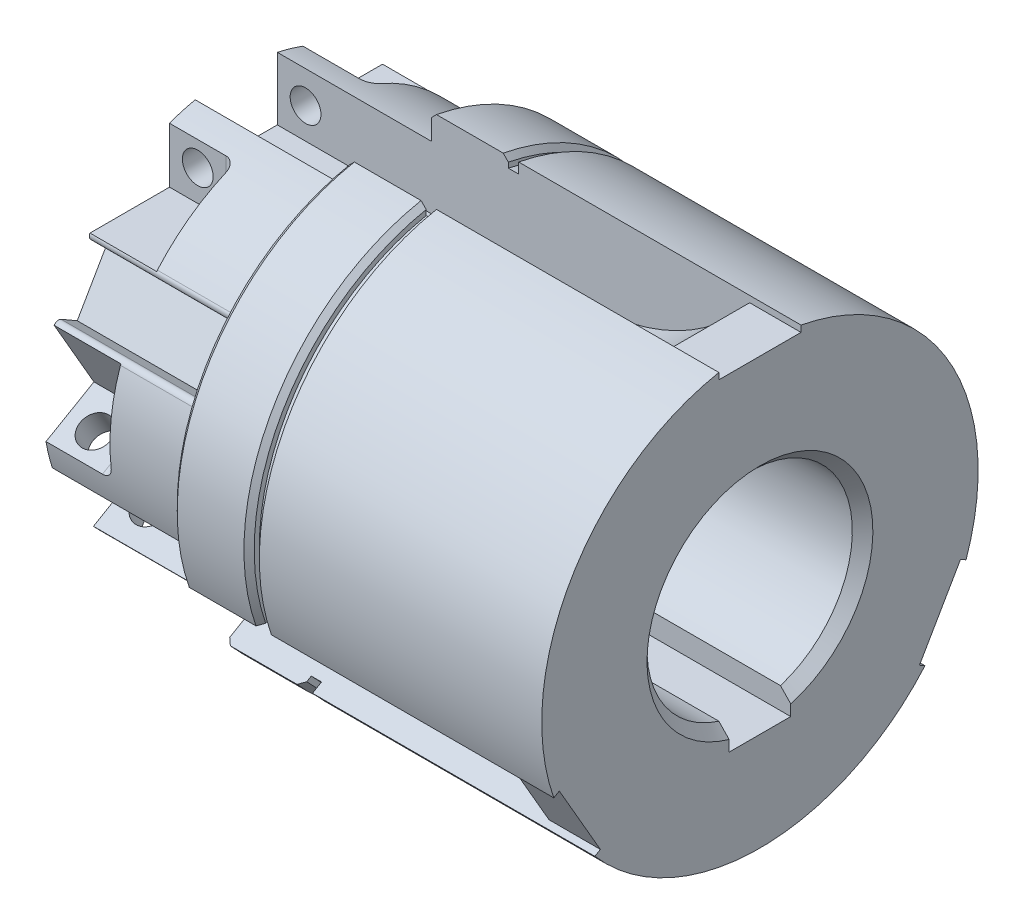
SolidWorks part; units mm, degrees
material "1.0060 (E335)"
ref_plane "Front Plane" through (0, 0, 0) normal (0, 0, 1) x (1, 0, 0)
ref_plane "Top Plane" through (0, 0, 0) normal (0, 1, 0) x (1, 0, 0)
ref_plane "Right Plane" through (0, 0, 0) normal (1, 0, 0) x (0, 0, -1)
sketch "Sketch1" plane through (0, 0, 0) normal (0, 0, 1) x (1, 0, 0)
  line L0 (-534.701, 0) -> (26200.3507, 0) construction
  line L1 (0, 20) -> (0, 42.5)
  line L2 (0, 20) -> (-102, 20)
  line L3 (0, 42.5) -> (-55, 42.5)
  line L4 (-55, 42.5) -> (-55, 40.5)
  line L5 (-55, 40.5) -> (-57, 40.5)
  line L6 (-57, 40.5) -> (-57, 42.5)
  line L7 (-57, 42.5) -> (-72, 42.5)
  line L8 (-72, 42.5) -> (-72, 37.6)
  line L9 (-72, 37.6) -> (-102, 37.6)
  line L10 (-102, 37.6) -> (-102, 20)
  dimension "D1" = 40
  dimension "D2" = 75.2
  dimension "D3" = 2
  dimension "D4" = 2
  dimension "D5" = 15
  dimension "D7" = 85
  dimension "D8" = 30
  dimension "D9" = 55
revolve "Revolve1" add sketch "Sketch1" angle 360 about L0
sketch "Sketch3" plane through (0, 0, 0) normal (0, 0, 1) x (1, 0, 0)
  line L0 (-102, 24.5) -> (-42, 24.5)
  line L1 (-102, 37.6) -> (-102, -37.6) construction
  line L2 (0, 42.5) -> (-55, 42.5) construction
  line L3 (0, 42.5) -> (-55, 42.5)
  line L4 (-57, -42.5) -> (-57, 42.5) construction
  line L5 (-55, 42.5) -> (-55, -42.5) construction
  line L6 (-57, 40.5) -> (-57, 42.5)
  line L7 (-55, 42.5) -> (-55, 40.5)
  line L8 (-55, 40.5) -> (-57, 40.5) construction
  line L9 (-55, 40.5) -> (-57, 40.5)
  line L10 (-72, 37.6) -> (-102, 37.6) construction
  line L11 (-72, 42.5) -> (-72, -42.5) construction
  line L12 (-57, 42.5) -> (-72, 42.5) construction
  line L13 (-72, 37.6) -> (-102, 37.6)
  line L14 (-72, 42.5) -> (-72, 37.6)
  line L15 (-57, 42.5) -> (-72, 42.5)
  line L16 (-102, 37.6) -> (-102, 24.5)
  line L17 (-10, 40.5) -> (0, 40.5)
  line L18 (0, -42.5) -> (0, 42.5) construction
  line L19 (0, 40.5) -> (0, 42.5)
  arc A0 (-42, 24.5) -> (-10, 40.5) centre (-42, 64.5) ccw
  dimension "D2" = 40
  dimension "D1" = 18
  dimension "D3" = 2
  dimension "D4" = 60
extrude "Cut-Extrude1" cut sketch "Sketch3" against normal mid plane 16
pattern_circular "CirPattern1" count 3 over 360 about axis through (0, 0, 0) along (1, 0, 0) of "Cut-Extrude1"
sketch "Sketch4" plane through (-102, 0, 0) normal (-1, 0, 0) x (0, 0, 1)
  line L0 (-13, 35.2812) -> (-13, 24.5)
  line L1 (-13, 24.5) -> (-28.5221, 24.5)
  line L2 (-8, 24.5) -> (8, 24.5) construction
  line L3 (0, -1000) -> (0, 49000) construction
  line L4 (-8, 24.5) -> (-8, 40.5) construction
  line L5 (13, 35.2812) -> (13, 24.5)
  line L6 (13, 24.5) -> (28.5221, 24.5)
  arc A0 (-8, 36.7391) -> (-35.817, -11.4413) centre (0, 0) ccw construction
  arc A1 (-8, 36.7391) -> (-35.817, -11.4413) centre (0, 0) ccw construction
  arc A2 (-13, 35.2812) -> (-28.5221, 24.5) centre (0, 0) ccw
  arc A3 (13, 35.2812) -> (28.5221, 24.5) centre (0, 0) cw
  dimension "D1" = 5
extrude "Cut-Extrude2" cut sketch "Sketch4" against normal blind 13
fillet "Fillet1" radius 2 2 edges at (-89, 29.8906, -13) (-89, 29.8906, 13)
sketch "Sketch6" plane through (0, 0, 13) normal (0, 0, 1) x (1, 0, 0)
  line L0 (-91, 24.5) -> (-102, 24.5) construction
  circle A0 centre (-96.5, 30.5) radius 3
  point P2 (-96.5, 24.5)
  dimension "D1" = 6
  dimension "D2" = 6
extrude "Cut-Extrude3" cut sketch "Sketch6" against normal up to surface (26 mm away) up to face at (-96.5, 29.8906, -13)
pattern_circular "CirPattern2" count 3 over 360 about axis through (0, 0, 0) along (1, 0, 0) of "Cut-Extrude2", "Fillet1", "Cut-Extrude3"
sketch "Sketch7" plane through (-102, 0, 0) normal (-1, 0, 0) x (0, 0, 1)
  line L0 (0, -1000) -> (0, 49000) construction
  line L1 (-6, -37.1182) -> (-6, -32.3)
  line L2 (-6, -32.3) -> (6, -32.3)
  line L3 (6, -32.3) -> (6, -37.1182)
  arc A0 (-27.817, -25.2977) -> (27.817, -25.2977) centre (0, 0) ccw construction
  arc A1 (-6.9566, -36.9509) -> (6.9566, -36.9509) centre (0, 0) ccw construction
  arc A2 (-6, -37.1182) -> (6, -37.1182) centre (0, 0) ccw
  point P8 (0, -32.3)
  dimension "D1" = 12
  dimension "D2" = 32.3
extrude "Cut-Extrude4" cut sketch "Sketch7" against normal up to surface (30 mm away) up to face at (-72, -33.299, 0)
fillet "Fillet2" radius 1 2 edges at (-87, -37.1182, 6) (-87, -37.1182, -6)
pattern_circular "CirPattern3" count 3 over 360 about axis through (0, 0, 0) along (1, 0, 0) of "Cut-Extrude4", "Fillet2"
ref_plane "Plane1" through (0, -23.3, 0) normal (0, 1, 0) x (1, 0, 0)
sketch "Sketch9" plane through (0, -23.3, 0) normal (0, 1, 0) x (1, 0, 0)
  line L0 (-102, 8) -> (-102, -8) construction
  line L1 (-102, -6) -> (0, -6)
  line L2 (-102, -6) -> (-102, 6)
  line L3 (-102, 6) -> (0, 6)
  line L4 (0, -6) -> (0, 6)
  line L5 (0, 8) -> (0, -8) construction
  point P8 (-102, 0)
  dimension "D1" = 12
extrude "Cut-Extrude5" cut sketch "Sketch9" along normal up to next
chamfer "Chamfer2" distance 2 angle 45 2 edges at (0, 20, 0) (-102, 20, 0)
chamfer "Chamfer3" distance 1 angle 45 6 edges at (-57, 21.25, -36.8061) (-72, 21.25, -36.8061) (-57, -42.5, 0) (-72, -42.5, 0) (-57, 21.25, 36.8061) (-72, 21.25, 36.8061)
